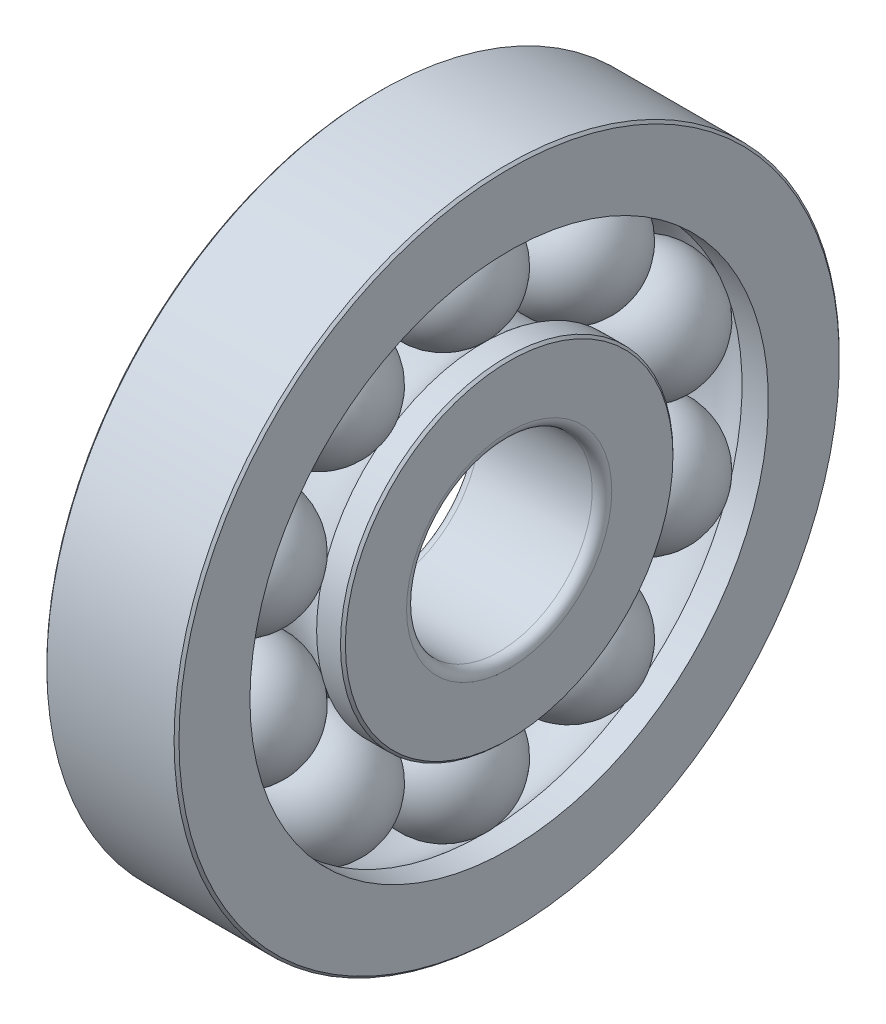
SolidWorks part; units mm, degrees
material "Wrought Copper"
ref_plane "Front Plane" through (0, 0, 0) normal (0, 0, 1) x (1, 0, 0)
ref_plane "Top Plane" through (0, 0, 0) normal (0, 1, 0) x (1, 0, 0)
ref_plane "Right Plane" through (0, 0, 0) normal (1, 0, 0) x (0, 0, -1)
sketch "Sketch1" plane through (0, 0, 0) normal (0, 0, 1) x (1, 0, 0)
  line L0 (0, 31.6691) -> (0, -38.4871) construction
  line L1 (-60.917, 0) -> (58.9414, 0) construction
  line L2 (-12.5, 0) -> (12.5, 0)
  arc A0 (12.5, 0) -> (-12.5, 0) centre (0, 0) ccw
  dimension "D1" = 25
revolve "Revolve4" add sketch "Sketch1" angle 360 about L1
ref_plane "Plane1" through (0, 0, 0) normal (0, 0, 1) x (1, 0, 0)
sketch "Sketch2" plane through (0, 0, 0) normal (0, 0, 1) x (1, 0, 0)
  line L0 (-22.8511, 0) -> (-12.5, 0) construction
  line L1 (0, 29.3317) -> (0, 9.5) construction
  line L2 (8.124, -9.5) -> (13.5, -9.5)
  line L3 (-13.5, 24.5) -> (13.5, 24.5)
  line L4 (-13.5, 24.5) -> (-13.5, 9.5)
  line L5 (-13.5, 9.5) -> (-8.124, 9.5)
  line L6 (13.5, 24.5) -> (13.5, 9.5)
  line L7 (-13.5, 24.5) -> (13.5, 9.5) construction
  line L8 (-13.5, 9.5) -> (13.5, 24.5) construction
  line L9 (-13.5, -9.5) -> (-8.124, -9.5)
  line L10 (-13.5, -9.5) -> (-13.5, -24.5)
  line L11 (-13.5, -24.5) -> (13.5, -24.5)
  line L12 (13.5, -9.5) -> (13.5, -24.5)
  line L13 (-13.5, -9.5) -> (13.5, -24.5) construction
  line L14 (-13.5, -24.5) -> (13.5, -9.5) construction
  line L15 (-12.5, 0) -> (12.5, 0)
  line L16 (-34.4922, -43.4691) -> (52.2637, -43.4691) construction
  line L17 (0, -9.5) -> (0, -30.1987) construction
  line L19 (8.124, 9.5) -> (13.5, 9.5)
  arc A0 (-8.124, -9.5) -> (8.124, -9.5) centre (0, 0) ccw
  arc A1 (12.5, 0) -> (-12.5, 0) centre (0, 0) ccw
  arc A2 (8.124, 9.5) -> (-8.124, 9.5) centre (0, 0) ccw
  point P5 (0, 17)
  point P10 (0, -17)
  dimension "D1" = 15
  dimension "D2" = 27
  dimension "D3" = 15
  dimension "D4" = 27
  dimension "D5" = 17
  dimension "D6" = 17
  dimension "D7" = 0
revolve "Revolve5" add sketch "Sketch2" angle 360 about L16
pattern_circular "CirPattern1" count 10 over 360 about axis through (0, -43.4691, 0) along (1, 0, 0) of bodies 101
chamfer "Chamfer1" distance 0.5 angle 45 1 edges at (13.5, -43.4691, 67.9691)
chamfer "Chamfer2" distance 0.5 angle 45 1 edges at (13.5, -43.4691, 33.9691)
fillet "Fillet1" radius 2 2 edges at (-13.5, -43.4691, 18.9691) (13.5, -43.4691, 18.9691)
chamfer "Chamfer3" distance 0.5 angle 45 1 edges at (-13.5, -43.4691, 67.9691)
chamfer "Chamfer4" distance 0.5 angle 45 1 edges at (-13.5, -43.4691, 33.9691)
